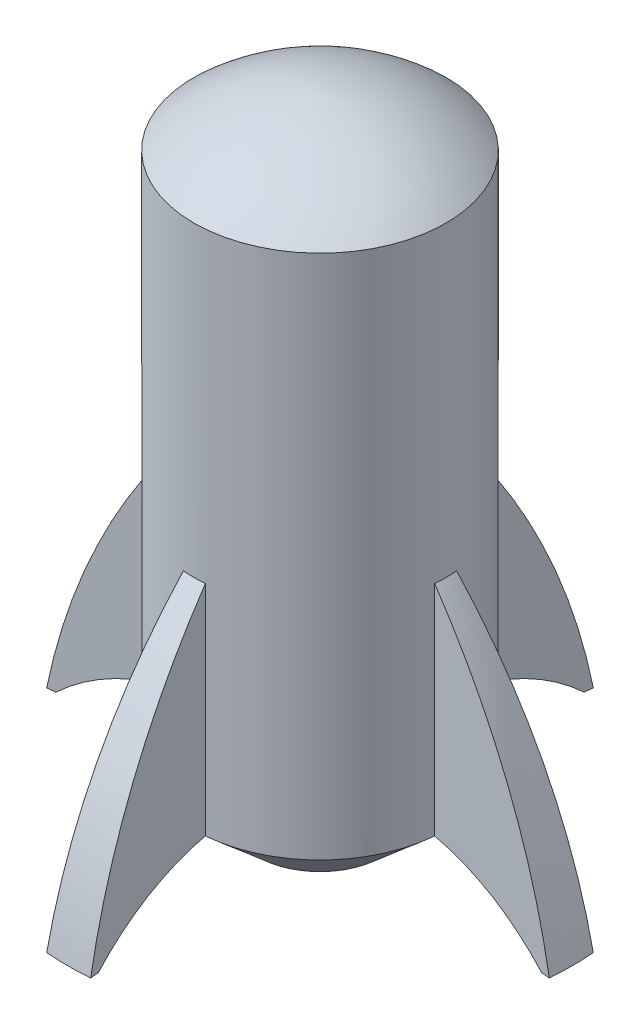
SolidWorks part; units mm, degrees
ref_plane "Front Plane" through (0, 0, 0) normal (0, 0, 1) x (1, 0, 0)
ref_plane "Top Plane" through (0, 0, 0) normal (0, 1, 0) x (1, 0, 0)
ref_plane "Right Plane" through (0, 0, 0) normal (1, 0, 0) x (0, 0, -1)
sketch "Sketch1" plane through (0, 0, 0) normal (1, 0, 0) x (0, 0, -1)
  line L0 (0, 0) -> (0, 150) construction
  line L1 (0, 0) -> (15, 0)
  line L2 (15, 0) -> (30, 13)
  line L3 (30, 13) -> (30, 138)
  line L4 (0, 0) -> (0, 150) construction
  line L5 (28, 13.9133) -> (28, 137.0698)
  line L6 (14.2539, 2) -> (28, 13.9133)
  line L7 (0, 2) -> (14.2539, 2)
  line L8 (0, 150) -> (0, 147.9972)
  line L9 (0, 2) -> (0, 0)
  arc A0 (0, 150) -> (30, 138) centre (-2.5735, 100.0663) cw
  arc A1 (0, 147.9972) -> (28, 137.0698) centre (-2.5735, 100.0663) cw
  arc A2 (-0.1029, 148.0027) -> (28, 137.0698) centre (-2.5735, 100.0663) cw construction
  dimension "D5" = 50
  dimension "D1" = 150
  dimension "D2" = 15
  dimension "D3" = 125
  dimension "D4" = 30
  dimension "D6" = 12
  dimension "D7" = 2
revolve "Revolve1" add sketch "Sketch1" angle 360 about L0
sketch "Sketch2" plane through (0, 0, 0) normal (1, 0, 0) x (0, 0, -1)
  line L0 (30, 13) -> (30, 138) construction
  line L1 (30, 65) -> (30, 13)
  line L2 (0, 0) -> (0, 150) construction
  line L3 (-15, 0) -> (15, 0) construction
  line L4 (0, 0) -> (74.7297, 0) construction
  line L5 (60, 0) -> (58, 0)
  arc A0 (30, 65) -> (60, 0) centre (-87.2593, -28.5428) cw
  arc A2 (30, 13) -> (58, 0) centre (23.9728, -36.6354) cw
  dimension "D1" = 58
  dimension "D2" = 150
  dimension "D5" = 50
  dimension "D3" = 65
  dimension "D4" = 60
revolve "Revolve2" add sketch "Sketch2" angle 10 mid plane about L2
pattern_circular "CirPattern1" count 4 over 360 about axis through (0, 0, 0) along (0, -1, 0) of "Revolve2"
